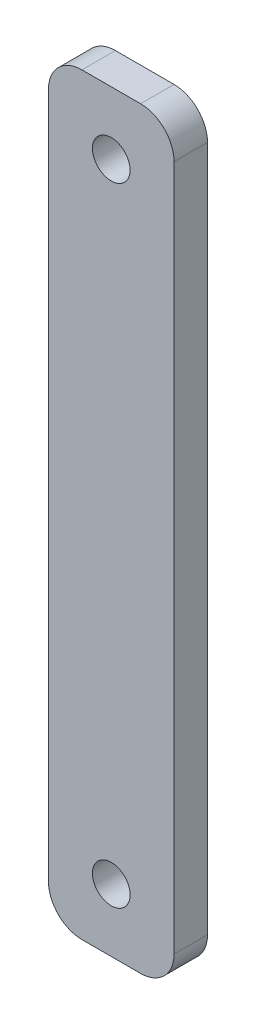
SolidWorks part; units mm, degrees
ref_plane "Front Plane" through (0, 0, 0) normal (0, 0, 1) x (1, 0, 0)
ref_plane "Top Plane" through (0, 0, 0) normal (0, 1, 0) x (1, 0, 0)
ref_plane "Right Plane" through (0, 0, 0) normal (1, 0, 0) x (0, 0, -1)
sketch "Sketch1" plane through (0, 0, 0) normal (0, 0, 1) x (1, 0, 0)
  line L0 (7.5, 45) -> (-7.5, -45) construction
  line L1 (-3.5, 45) -> (3.5, 45)
  line L2 (-7.5, 41) -> (-7.5, -41)
  line L3 (-3.5, -45) -> (3.5, -45)
  line L4 (7.5, 41) -> (7.5, -41)
  line L5 (7.5, -45) -> (-7.5, 45) construction
  line L6 (0, 0) -> (0, 84.346) construction
  line L7 (0, 0) -> (62.3193, 0) construction
  arc A1 (-7.5, -41) -> (-3.5, -45) centre (-3.5, -41) ccw
  arc A2 (3.5, -45) -> (7.5, -41) centre (3.5, -41) ccw
  arc A3 (3.5, 45) -> (7.5, 41) centre (3.5, 41) cw
  arc A4 (-3.5, 45) -> (-7.5, 41) centre (-3.5, 41) ccw
  circle A5 centre (0, 37.5) radius 2.25
  circle A6 centre (0, -37.5) radius 2.25
  point P5 (0, 0)
  dimension "D3" = 4
  dimension "D4" = 4.5
  dimension "D5" = 37.5
  dimension "D1" = 15
  dimension "D2" = 90
extrude "Boss-Extrude2" add sketch "Sketch1" along normal blind 4
